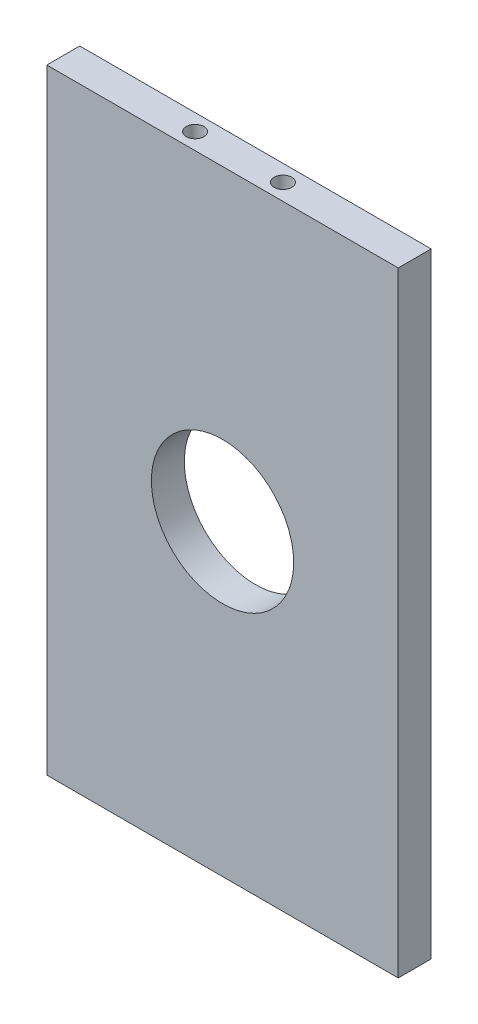
SolidWorks part; units mm, degrees
ref_plane "Front" through (0, 0, 0) normal (0, 0, 1) x (1, 0, 0)
ref_plane "Top" through (0, 0, 0) normal (0, 1, 0) x (1, 0, 0)
ref_plane "Right" through (0, 0, 0) normal (1, 0, 0) x (0, 0, -1)
sketch "Sketch1" plane through (0, 0, 0) normal (0, 0, 1) x (1, 0, 0)
  line L1 (101.6, -152.4) -> (-101.6, -152.4)
  line L2 (101.6, -152.4) -> (101.6, 152.4)
  line L3 (101.6, 152.4) -> (-101.6, 152.4)
  line L4 (-101.6, -152.4) -> (-101.6, 152.4)
  line L5 (101.6, -152.4) -> (-101.6, 152.4) construction
  line L6 (101.6, 152.4) -> (-101.6, -152.4) construction
  point P0 (0, 0)
  dimension "D1" = 203.2
  dimension "D2" = 304.8
extrude "Boss-Extrude1" add sketch "Sketch1" along normal blind 9.525
sketch "Sketch2" plane through (0, 0, 9.525) normal (0, 0, 1) x (1, 0, 0)
  circle A0 centre (0, 0) radius 20.574
  dimension "D1" = 41.148
extrude "Cut-Extrude1" cut sketch "Sketch2" against normal up to next
sketch "Sketch3" plane through (0, 0, 9.525) normal (0, 0, 1) x (1, 0, 0)
  line L0 (101.6, -152.4) -> (101.6, 152.4) construction
  line L1 (-101.6, -152.4) -> (101.6, -152.4)
  line L2 (-101.6, -152.4) -> (-101.6, -88.9)
  line L3 (-101.6, -88.9) -> (101.6, -88.9)
  line L4 (101.6, -152.4) -> (101.6, -88.9)
  line L6 (-101.6, 152.4) -> (101.6, 152.4)
  line L7 (-101.6, 152.4) -> (-101.6, 88.9)
  line L8 (-101.6, 88.9) -> (101.6, 88.9)
  line L9 (101.6, 152.4) -> (101.6, 88.9)
  dimension "D1" = 177.8
extrude "Cut-Extrude2" cut sketch "Sketch3" against normal up to next
hole_wizard "1/4-20 Tapped Hole1" positions "Sketch4" profile "Sketch5" tap size "1/4-20" standard "ANSI Inch"
sketch "Sketch4" plane through (0, 88.9, 0) normal (0, 1, 0) x (1, 0, 0)
  line L0 (-101.6, 0) -> (-101.6, -9.525) construction
  line L1 (-12.7, -4.7625) -> (12.7, -4.7625) construction
  line L3 (101.6, 0) -> (-101.6, 0) construction
  point P0 (-12.7, -4.7625)
  point P2 (12.7, -4.7625)
  point P7 (-101.6, -4.7625)
  point P11 (0, -4.7625)
  point P14 (0, 0)
  dimension "D1" = 25.4
sketch "Sketch5" plane through (-12.7, 88.9, 4.7625) normal (1, 0, 0) x (0, 0, 1)
  line L0 (0, 0) -> (0, 20.5838)
  line L1 (0, 20.5838) -> (2.5527, 19.05)
  line L2 (2.5527, 19.05) -> (2.5527, 0)
  line L5 (2.5527, 0) -> (0, 0)
  line L10 (0, 20.5838) -> (-2.5527, 19.05) construction
  line L11 (0, -6.35) -> (0, 107.95) construction
  dimension "Tap Drill Dia." = 5.1054
  dimension "Tap Drill Depth" = 19.05
  dimension "Drill Angle" = 118
cosmetic thread "Hole Thread1" parameters "D1"=15.24, "D2"=6.35
cosmetic thread "Hole Thread2" parameters "D1"=15.24, "D2"=6.35
mirror "Mirror1" about plane through (0, 0, 0) normal (0, 1, 0) of "1/4-20 Tapped Hole1"
cosmetic thread "Hole Thread3" parameters "D1"=15.24, "D2"=6.35
cosmetic thread "Hole Thread4" parameters "D1"=15.24, "D2"=6.35
sketch "Sketch6" plane through (0, 0, 9.525) normal (0, 0, 1) x (1, 0, 0)
  line L0 (101.6, -88.9) -> (-101.6, -88.9) construction
  line L1 (-101.6, 88.9) -> (-50.8, 88.9)
  line L2 (-101.6, 88.9) -> (-101.6, -88.9)
  line L3 (-101.6, -88.9) -> (-50.8, -88.9)
  line L4 (-50.8, 88.9) -> (-50.8, -88.9)
  line L6 (101.6, 88.9) -> (50.8, 88.9)
  line L7 (101.6, 88.9) -> (101.6, -88.9)
  line L8 (101.6, -88.9) -> (50.8, -88.9)
  line L9 (50.8, 88.9) -> (50.8, -88.9)
  dimension "D1" = 50.8
extrude "Cut-Extrude3" cut sketch "Sketch6" against normal up to next
